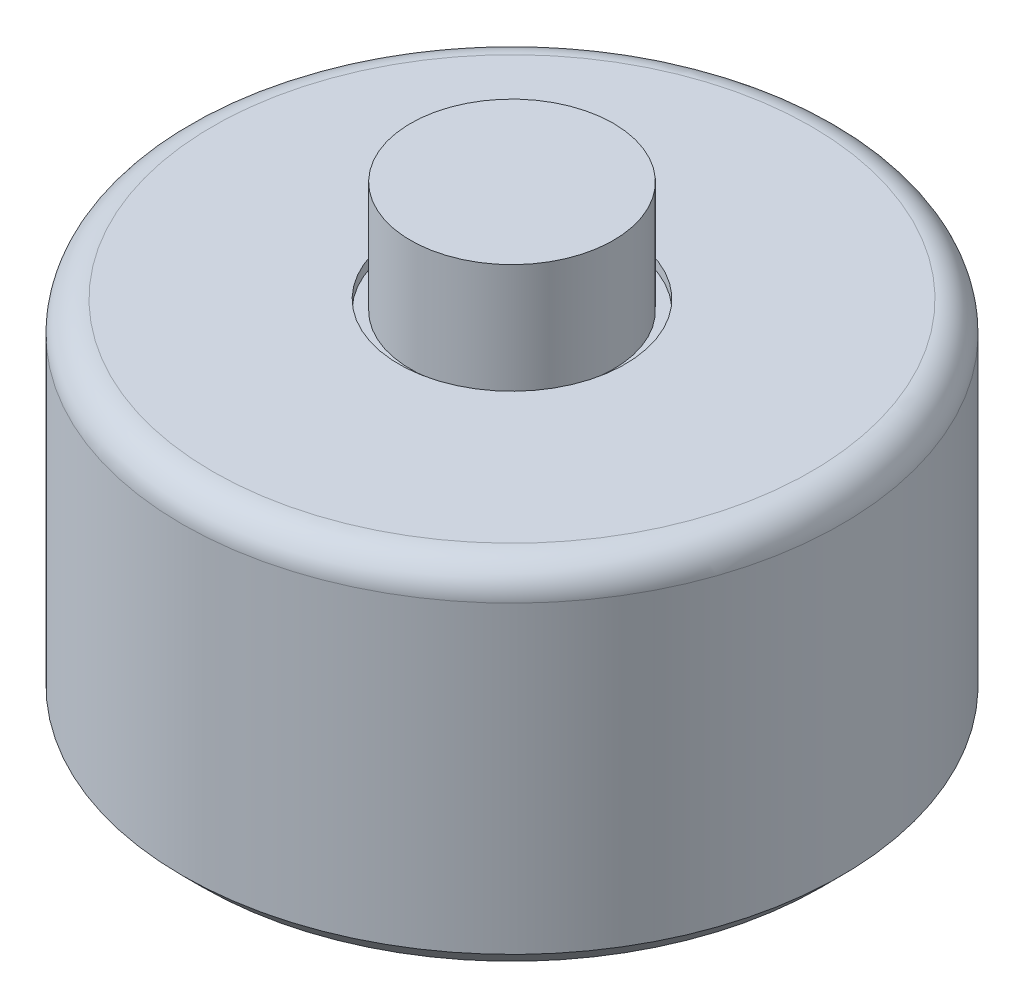
SolidWorks part; units mm, degrees
ref_plane "Front Plane" through (0, 0, 0) normal (0, 0, 1) x (1, 0, 0)
ref_plane "Top Plane" through (0, 0, 0) normal (0, 1, 0) x (1, 0, 0)
ref_plane "Right Plane" through (0, 0, 0) normal (1, 0, 0) x (0, 0, -1)
sketch "Sketch1" plane through (0, 0, 0) normal (0, 0, 1) x (1, 0, 0)
  line L0 (0, 0) -> (0, 11.43)
  line L1 (0, 11.43) -> (2.54, 11.43)
  line L2 (2.54, 11.43) -> (2.54, 8.89)
  line L4 (8.255, 8.89) -> (8.255, 0)
  line L5 (8.255, 0) -> (0, 0)
  line L6 (2.54, 8.89) -> (2.54, 8.636)
  line L7 (2.54, 8.636) -> (2.8321, 8.636)
  line L8 (2.8321, 8.636) -> (2.8321, 8.89)
  line L9 (2.8321, 8.89) -> (8.255, 8.89)
  dimension "D1" = 11.43
  dimension "D2" = 8.89
  dimension "D3" = 2.54
  dimension "D4" = 0.2921
  dimension "D5" = 0.254
  dimension "D6" = 8.255
revolve "Revolve1" add sketch "Sketch1" angle 360 about L0
fillet "Fillet1" radius 0.762 1 edges at (0, 8.89, -8.255)
chamfer "Chamfer1" distance 0.508 angle 45 1 edges at (0, 0, -8.255)
sketch "Sketch2" plane through (0, 0, 0) normal (0, -1, 0) x (1, 0, 0)
  line L1 (4.826, 0.5397) -> (6.731, 0.5398)
  line L2 (4.826, 0.5397) -> (4.826, -0.5397)
  line L3 (4.826, -0.5397) -> (6.731, -0.5397)
  line L4 (6.731, 0.5398) -> (6.731, -0.5397)
  point P4 (6.731, 0)
  dimension "D1" = 1.0795
  dimension "D2" = 1.905
  dimension "D3" = 4.826
extrude "Cut-Extrude1" cut sketch "Sketch2" against normal blind 0.5715
pattern_circular "CirPattern1" count 4 over 360 about axis through (0, 0, 0) along (0, 1, 0) of "Cut-Extrude1"
